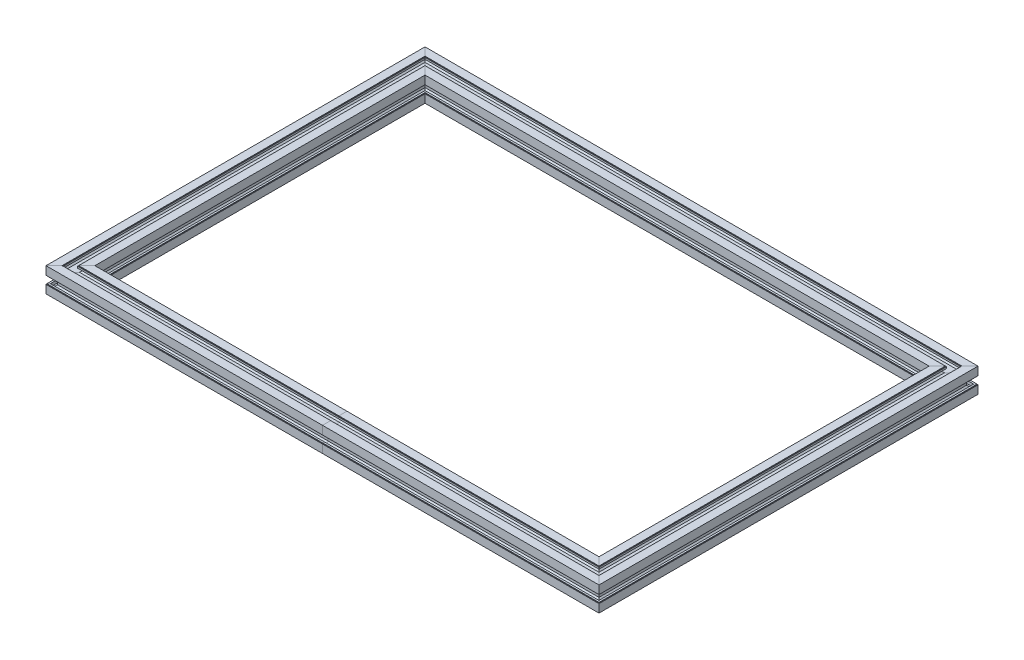
SolidWorks part; units mm, degrees
ref_plane "Alzado" through (0, 0, 0) normal (0, 0, 1) x (1, 0, 0)
ref_plane "Planta" through (0, 0, 0) normal (0, 1, 0) x (1, 0, 0)
ref_plane "Vista lateral" through (0, 0, 0) normal (1, 0, 0) x (0, 0, -1)
sketch "Croquis1" plane through (0, 0, 0) normal (0, 1, 0) x (1, 0, 0)
  line L1 (-210.93, 141.5) -> (210.93, 141.5)
  line L2 (-210.93, 141.5) -> (-210.93, -141.5)
  line L3 (-210.93, -141.5) -> (210.93, -141.5)
  line L4 (210.93, 141.5) -> (210.93, -141.5)
  line L5 (-210.93, 141.5) -> (210.93, -141.5) construction
  line L6 (-210.93, -141.5) -> (210.93, 141.5) construction
  point P0 (0, 0)
  dimension "D1" = 283
  dimension "D2" = 421.86
sketch "Croquis2" plane through (0, 0, 0) normal (1, 0, 0) x (0, 0, -1)
  line L0 (-144.8482, 9.7512) -> (-144.8482, 9.3912)
  line L1 (-141.4985, 12.2688) -> (-141.4985, -11.1058) construction
  line L2 (-152.734, 0.0006) -> (-128.618, 0.0006) construction
  line L3 (-131.7476, 3.186) -> (-132.1076, 3.1858)
  line L4 (-151.2493, 3.186) -> (-151.2493, 9.7512)
  line L5 (-132.1076, 3.1858) -> (-132.1073, 2.6808)
  line L6 (-132.1073, 2.6808) -> (-133.4773, 2.6799)
  line L7 (-144.8482, 9.3912) -> (-144.3432, 9.3912)
  line L8 (-144.3432, 9.3912) -> (-144.3432, 8.0212)
  line L9 (-144.3432, 8.0212) -> (-146.6782, 8.0212)
  line L10 (-146.6782, 8.0212) -> (-146.6782, 6.7212)
  line L11 (-146.6782, 6.7212) -> (-145.1217, 5.1638)
  line L12 (-133.4773, 2.6799) -> (-133.4787, 5.0149)
  line L13 (-133.4787, 5.0149) -> (-134.7787, 5.0141)
  line L14 (-151.2493, 9.7512) -> (-144.8482, 9.7512)
  line L15 (-134.7787, 5.0141) -> (-136.3352, 3.4567)
  line L16 (-131.7476, 9.7512) -> (-138.1488, 9.7512)
  line L17 (-148.2182, 5.0141) -> (-146.6617, 3.4567)
  line L18 (-149.5182, 5.0149) -> (-148.2182, 5.0141)
  line L19 (-149.5196, 2.6799) -> (-149.5182, 5.0149)
  line L20 (-150.8896, 2.6808) -> (-149.5196, 2.6799)
  line L21 (-150.8893, 3.1858) -> (-150.8896, 2.6808)
  line L22 (-136.3188, 6.7212) -> (-137.8752, 5.1638)
  line L23 (-151.2493, 3.186) -> (-150.8893, 3.1858)
  line L24 (-136.3188, 8.0212) -> (-136.3188, 6.7212)
  line L25 (-138.6538, 8.0212) -> (-136.3188, 8.0212)
  line L26 (-138.6538, 9.3912) -> (-138.6538, 8.0212)
  line L27 (-138.1488, 9.3912) -> (-138.6538, 9.3912)
  line L28 (-131.7476, 3.186) -> (-131.7476, 9.7512)
  line L29 (-138.1488, 9.7512) -> (-138.1488, 9.3912)
  line L30 (-151.2493, -3.1847) -> (-150.8893, -3.1845)
  line L31 (-150.8893, -3.1845) -> (-150.8896, -2.6795)
  line L32 (-150.8896, -2.6795) -> (-149.5196, -2.6787)
  line L33 (-149.5196, -2.6787) -> (-149.5182, -5.0137)
  line L34 (-149.5182, -5.0137) -> (-148.2182, -5.0129)
  line L35 (-148.2182, -5.0129) -> (-146.6617, -3.4555)
  line L36 (-151.2493, -9.75) -> (-144.8482, -9.75)
  line L37 (-146.6782, -6.72) -> (-145.1217, -5.1625)
  line L38 (-146.6782, -8.02) -> (-146.6782, -6.72)
  line L39 (-144.3432, -8.02) -> (-146.6782, -8.02)
  line L40 (-144.3432, -9.39) -> (-144.3432, -8.02)
  line L41 (-144.8482, -9.39) -> (-144.3432, -9.39)
  line L42 (-151.2493, -3.1847) -> (-151.2493, -9.75)
  line L43 (-144.8482, -9.75) -> (-144.8482, -9.39)
  line L44 (-138.1488, -9.75) -> (-138.1488, -9.39)
  line L45 (-138.1488, -9.39) -> (-138.6538, -9.39)
  line L46 (-138.6538, -9.39) -> (-138.6538, -8.02)
  line L47 (-131.7476, -3.1847) -> (-131.7476, -9.75)
  line L48 (-138.6538, -8.02) -> (-136.3188, -8.02)
  line L49 (-136.3188, -8.02) -> (-136.3188, -6.72)
  line L50 (-136.3188, -6.72) -> (-137.8752, -5.1625)
  line L51 (-131.7476, -9.75) -> (-138.1488, -9.75)
  line L52 (-134.7787, -5.0129) -> (-136.3352, -3.4555)
  line L53 (-133.4787, -5.0137) -> (-134.7787, -5.0129)
  line L54 (-133.4773, -2.6787) -> (-133.4787, -5.0137)
  line L55 (-132.1073, -2.6795) -> (-133.4773, -2.6787)
  line L56 (-132.1076, -3.1845) -> (-132.1073, -2.6795)
  line L57 (-131.7476, -3.1847) -> (-132.1076, -3.1845)
  line L58 (-146.6617, -3.4555) -> (-146.6617, 3.4567)
  line L59 (-145.1217, 5.1638) -> (-137.8752, 5.1638)
  line L60 (-136.3352, 3.4567) -> (-136.3352, -3.4555)
  line L61 (-145.1217, -5.1625) -> (-137.8752, -5.1625)
  circle A0 centre (-141.4985, 0.0006) radius 2.5
  point P72 (0, 0)
  dimension "D6" = 5
  dimension "D1" = 0.36
  dimension "D2" = 0.505
  dimension "D3" = 1.37
  dimension "D4" = 2.335
  dimension "D5" = 1.3
  dimension "D7" = 2.2019
sweep "Barrer1" add profiles "Croquis2" path "Croquis1"
